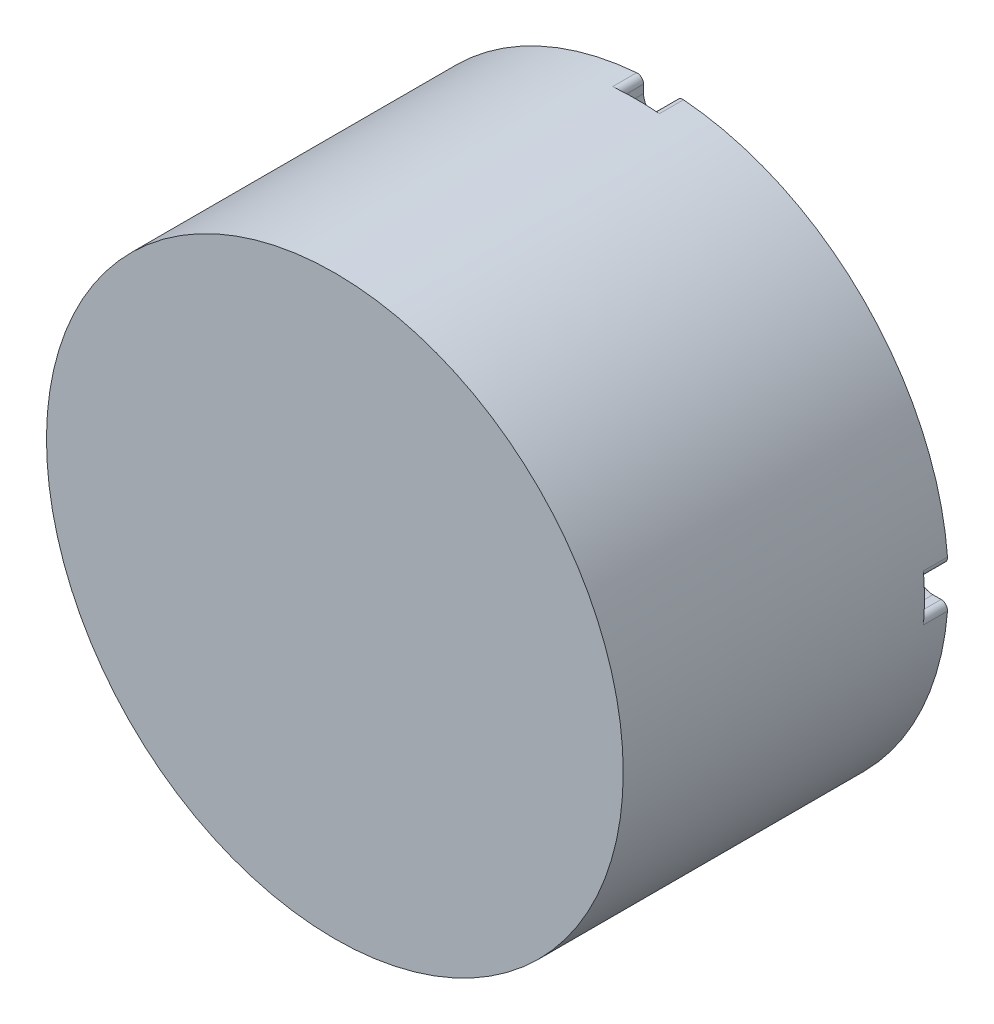
SolidWorks part; units mm, degrees
ref_plane "Front Plane" through (0, 0, 0) normal (0, 0, 1) x (1, 0, 0)
ref_plane "Top Plane" through (0, 0, 0) normal (0, 1, 0) x (1, 0, 0)
ref_plane "Right Plane" through (0, 0, 0) normal (1, 0, 0) x (0, 0, -1)
sketch "Sketch1" plane through (0, 0, 0) normal (0, 0, 1) x (1, 0, 0)
  circle A0 centre (0, 0) radius 90
  dimension "D1" = 180
extrude "Boss-Extrude1" add sketch "Sketch1" along normal blind 101.5
sketch "Sketch2" plane through (0, 0, 0) normal (0, 0, -1) x (-1, 0, 0)
  line L0 (-5.15, 89.8525) -> (-5.15, 85.15)
  line L1 (5.15, 89.8525) -> (5.15, 85.15)
  line L2 (0, 85.15) -> (0, 0) construction
  line L3 (0, 85.15) -> (0, 90) construction
  circle A0 centre (0, 0) radius 90 construction
  arc A1 (-5.15, 85.15) -> (5.15, 85.15) centre (0, 85.15) ccw
  arc A2 (-5.15, 89.8525) -> (5.15, 89.8525) centre (0, 0) cw
  point P7 (0, 80)
  circle M4 centre (0, 0) radius 90
  dimension "D1" = 10.3
  dimension "D2" = 10
extrude "Cut-Extrude1" cut sketch "Sketch2" against normal blind 7.5 contours L0 A1 L1 M4
fillet "Fillet1" radius 2 2 edges at (-5.15, 89.8525, 3.75) (5.15, 89.8525, 3.75)
hole_wizard "Tap Drill for M8 Tap1" positions "Sketch4" profile "Sketch5" hole size "M8" standard "ISO"
sketch "Sketch4" plane through (0, 0, 0) normal (0, 0, -1) x (-1, 0, 0)
  line L0 (60.1041, 60.1041) -> (0, 0) construction
  line L2 (0, 0) -> (0, 85.15) construction
  point P0 (60.1041, 60.1041)
  dimension "D1" = 85
  dimension "D2" = 45
sketch "Sketch5" plane through (-60.1041, 60.1041, 0) normal (1, 0, 0) x (0, 1, 0)
  line L0 (0, 0) -> (0, 15.5)
  line L1 (0, 15.5) -> (3.4, 13.4571)
  line L2 (3.4, 13.4571) -> (3.4, 0)
  line L5 (3.4, 0) -> (0, 0)
  line L10 (0, 15.5) -> (-3.4, 13.4571) construction
  line L11 (0, -6.35) -> (0, 107.95) construction
  dimension "Hole Dia." = 6.8
  dimension "Hole Depth" = 15.5
  dimension "Drill Angle" = 118
pattern_circular "CirPattern1" count 4 over 360 about axis through (0, 0, 0) along (0, 0, 1) of "Cut-Extrude1", "Fillet1", "Tap Drill for M8 Tap1"
sketch "Sketch6" plane through (0, 0, 0) normal (0, 0, -1) x (-1, 0, 0)
  circle A0 centre (0, 0) radius 75
  dimension "D1" = 150
extrude "Boss-Extrude2" add sketch "Sketch6" along normal blind 3
sketch "Sketch7" plane through (0, 0, -3) normal (0, 0, -1) x (-1, 0, 0)
  circle A0 centre (0, 0) radius 57
  dimension "D1" = 114
extrude "Boss-Extrude3" add sketch "Sketch7" along normal blind 3
sketch "Sketch8" plane through (0, 0, -6) normal (0, 0, -1) x (-1, 0, 0)
  circle A0 centre (0, 0) radius 17.5
  dimension "D1" = 35
extrude "Cut-Extrude2" cut sketch "Sketch8" against normal blind 10
sketch "Sketch9" plane through (0, 0, 4) normal (0, 0, -1) x (-1, 0, 0)
  circle A0 centre (0, 0) radius 10
  dimension "D1" = 20
extrude "Boss-Extrude4" add sketch "Sketch9" along normal blind 42
sketch "Sketch10" plane through (0, 0, -38) normal (0, 0, -1) x (-1, 0, 0)
  line L0 (-2.5, 9.6825) -> (-2.5, 6.8825)
  line L1 (-2.5, 6.8825) -> (2.5, 6.8825)
  line L2 (2.5, 6.8825) -> (2.5, 9.6825)
  line L3 (0, 0) -> (0, 6.8825) construction
  circle A0 centre (0, 0) radius 10 construction
  circle A1 centre (0, 0) radius 10 construction
  arc A2 (2.5, 9.6825) -> (-2.5, 9.6825) centre (0, 0) ccw
  dimension "D1" = 5
  dimension "D2" = 2.8
extrude "Cut-Extrude3" cut sketch "Sketch10" against normal blind 20
sketch "Sketch11" plane through (0, 6.8825, 0) normal (0, 1, 0) x (1, 0, 0)
  line L0 (2.5, 18) -> (-2.5, 18) construction
  line L1 (2.5, 18) -> (-2.5, 18) construction
  line L2 (2.5, 18) -> (-2.5, 18)
  arc A0 (-2.5, 18) -> (2.5, 18) centre (0, 18) ccw
extrude "Cut-Extrude4" cut sketch "Sketch11" along normal through all
